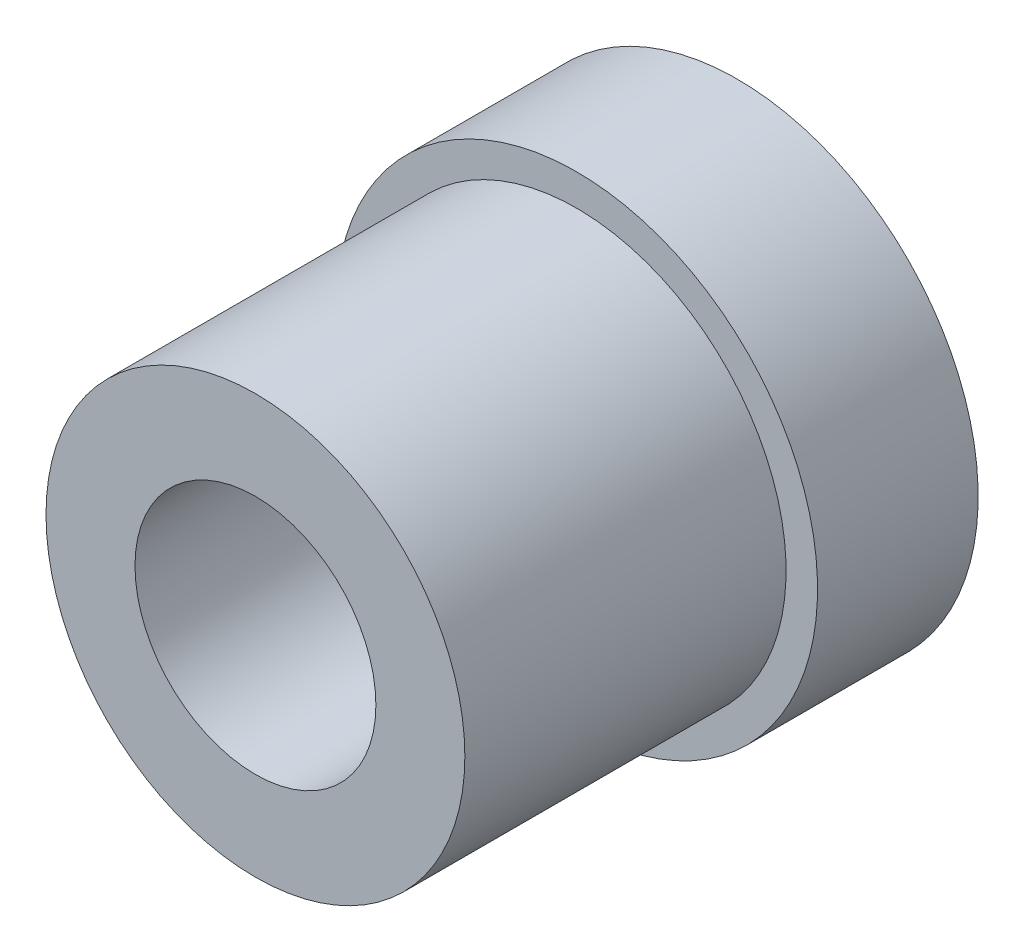
SolidWorks part; units mm, degrees
material "AISI 4130 Steel, normalized at 870C"
ref_plane "Front Plane" through (0, 0, 0) normal (0, 0, 1) x (1, 0, 0)
ref_plane "Top Plane" through (0, 0, 0) normal (0, 1, 0) x (1, 0, 0)
ref_plane "Right Plane" through (0, 0, 0) normal (1, 0, 0) x (0, 0, -1)
sketch "Sketch1" plane through (0, 0, 0) normal (0, 0, 1) x (1, 0, 0)
  circle A0 centre (0, 0) radius 9.525
  circle A1 centre (0, 0) radius 8.2804
  dimension "D1" = 19.05
  dimension "D2" = 1.2446
sketch "Sketch2" plane through (0, 0, 0) normal (0, 0, 1) x (1, 0, 0)
  circle A0 centre (0, 0) radius 8.2804 construction
  circle A1 centre (0, 0) radius 8.2804
  circle A2 centre (0, 0) radius 4.7625
  dimension "D1" = 9.525
extrude "Boss-Extrude1" add sketch "Sketch2" along normal blind 12.7
sketch "Sketch3" plane through (0, 0, 0) normal (0, 0, -1) x (-1, 0, 0)
  circle A0 centre (0, 0) radius 9.525 construction
  circle A1 centre (0, 0) radius 9.525
  circle A2 centre (0, 0) radius 4.7625 construction
  circle A3 centre (0, 0) radius 4.7625
extrude "Boss-Extrude2" add sketch "Sketch3" along normal blind 6.35
